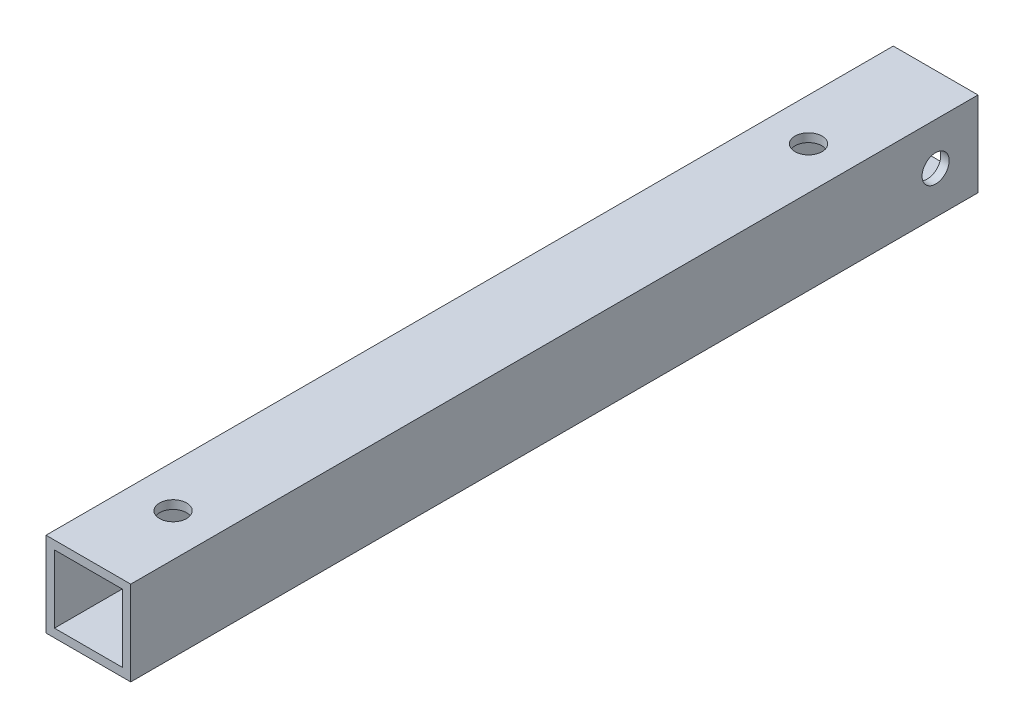
SolidWorks part; units mm, degrees
ref_plane "正面" through (0, 0, 0) normal (0, 0, 1) x (1, 0, 0)
ref_plane "平面" through (0, 0, 0) normal (0, 1, 0) x (1, 0, 0)
ref_plane "右側面" through (0, 0, 0) normal (1, 0, 0) x (0, 0, -1)
sketch "ｽｹｯﾁ1" plane through (0, 0, 0) normal (0, 0, 1) x (1, 0, 0)
  line L0 (-4, 4) -> (-4, -4)
  line L1 (-5, 5) -> (5, 5)
  line L2 (-5, 5) -> (-5, -5)
  line L3 (-5, -5) -> (5, -5)
  line L4 (5, 5) -> (5, -5)
  line L5 (-5, 5) -> (5, -5) construction
  line L6 (-5, -5) -> (5, 5) construction
  line L7 (-4, -4) -> (4, -4)
  line L8 (4, 4) -> (4, -4)
  line L9 (-4, 4) -> (4, 4)
  point P0 (0, 0)
  dimension "D1" = 10
  dimension "D2" = 10
  dimension "D3" = 1
extrude "ﾎﾞｽ - 押し出し1" add sketch "ｽｹｯﾁ1" along normal blind 100
sketch "ｽｹｯﾁ2" plane through (-5, 0, 0) normal (-1, 0, 0) x (0, 0, 1)
  line L0 (5.5, 0) -> (-5.5, 0) construction
  line L1 (0, -5.5) -> (0, 5.5) construction
  line L2 (100, 5) -> (100, -5) construction
  circle A0 centre (5, 0) radius 1.6
  circle A1 centre (95, 0) radius 1.6 construction
  dimension "D1" = 3.2
  dimension "D2" = 5
  dimension "D3" = 3.2
  dimension "D4" = 5
extrude "ｶｯﾄ - 押し出し1" cut sketch "ｽｹｯﾁ2" against normal through all
sketch "ｽｹｯﾁ3" plane through (0, 5, 0) normal (0, 1, 0) x (1, 0, 0)
  line L0 (0, -5.5) -> (0, 5.5) construction
  line L1 (-5.5, 0) -> (5.5, 0) construction
  circle A0 centre (0, -90) radius 1.6
  dimension "D1" = 3.2
  dimension "D2" = 90
extrude "ｶｯﾄ - 押し出し2" cut sketch "ｽｹｯﾁ3" against normal through all
sketch "ｽｹｯﾁ4" plane through (0, 5, 0) normal (0, 1, 0) x (1, 0, 0)
  line L0 (0, -5.5) -> (0, 5.5) construction
  line L1 (5, -100) -> (-5, -100) construction
  circle A0 centre (0, -50) radius 1.6
  dimension "D1" = 3.2
  dimension "D2" = 50
sketch "ｽｹｯﾁ5" plane through (0, 5, 0) normal (0, 1, 0) x (1, 0, 0)
  line L0 (0, -5.5) -> (0, 5.5) construction
  line L1 (-5.5, 0) -> (5.5, 0) construction
  circle A0 centre (0, -15) radius 1.6
  dimension "D1" = 3.2
  dimension "D2" = 15
extrude "ｶｯﾄ - 押し出し4" cut sketch "ｽｹｯﾁ5" against normal through all
